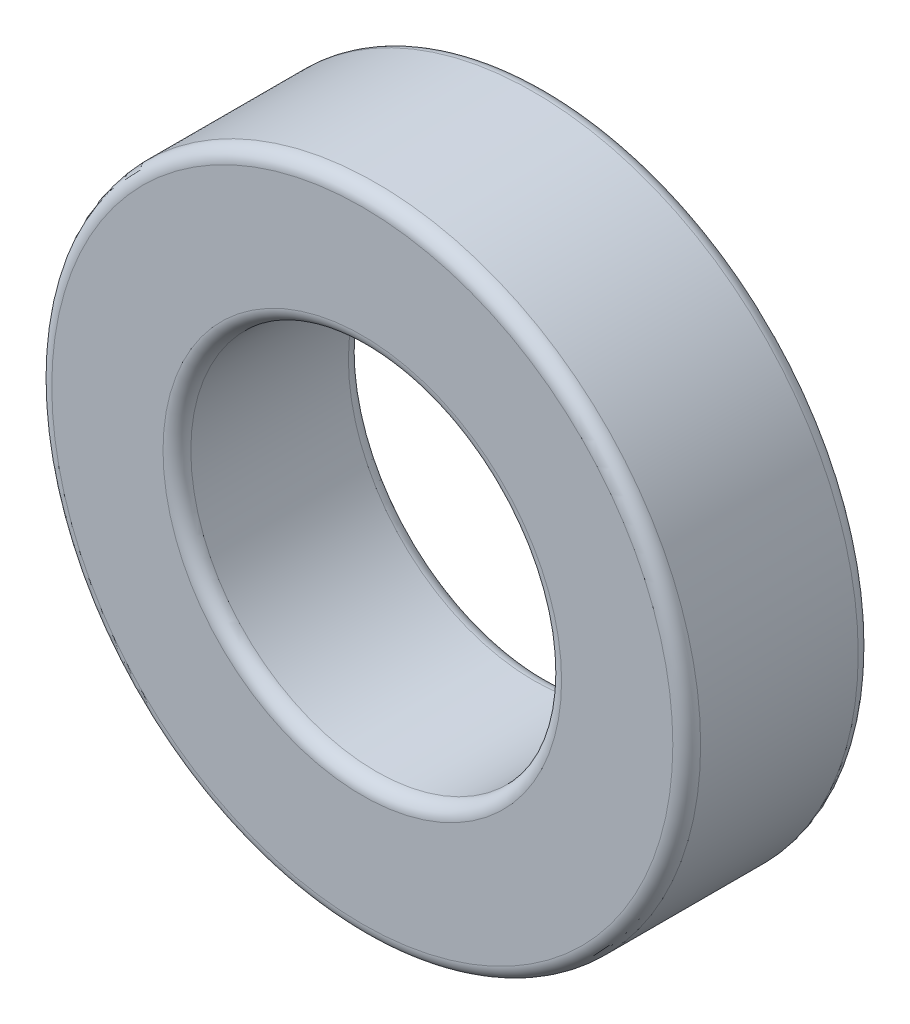
SolidWorks part; units mm, degrees
ref_plane "前视基准面" through (0, 0, 0) normal (0, 0, 1) x (1, 0, 0)
ref_plane "上视基准面" through (0, 0, 0) normal (0, 1, 0) x (1, 0, 0)
ref_plane "右视基准面" through (0, 0, 0) normal (1, 0, 0) x (0, 0, -1)
sketch "草图1" plane through (0, 0, 0) normal (0, 0, 1) x (1, 0, 0)
  circle A0 centre (0, 0) radius 4
  circle A1 centre (0, 0) radius 7
  dimension "D1" = 8
  dimension "D2" = 14
extrude "凸台-拉伸1" add sketch "草图1" along normal blind 4
fillet "圆角1" radius 0.3 4 edges at (4, 0, 0) (7, 0, 0) (4, 0, 4) (7, 0, 4)
